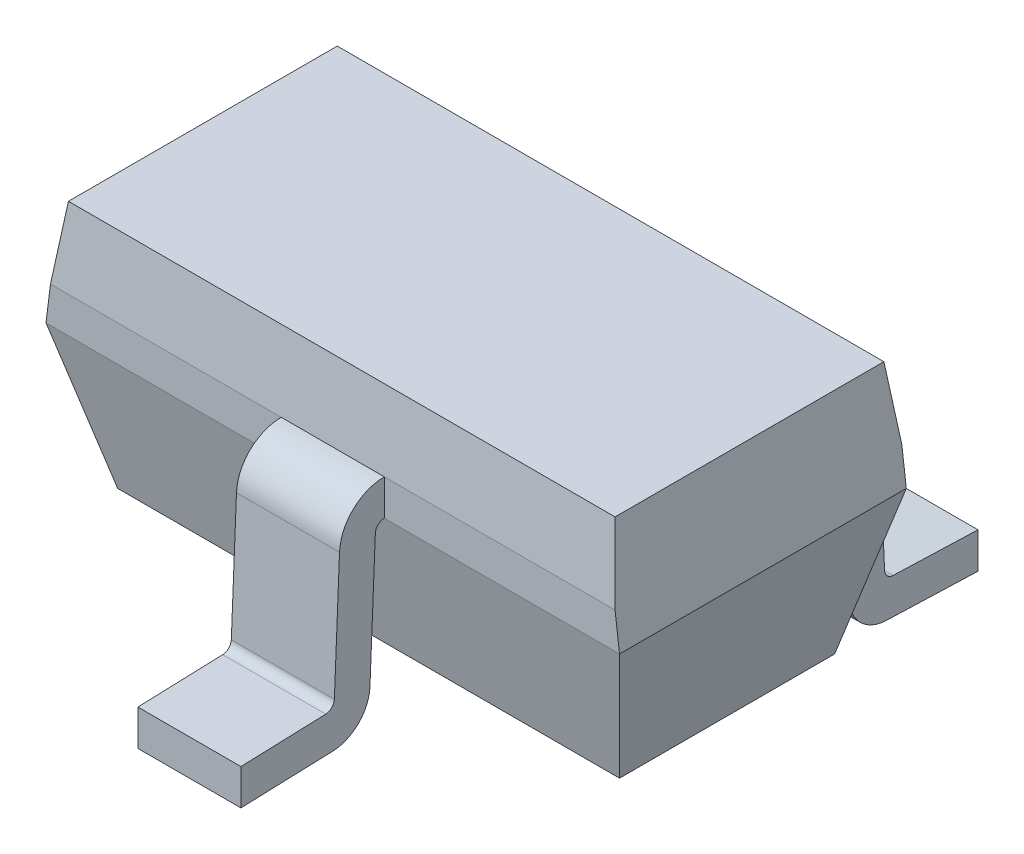
SolidWorks part; units mm, degrees
material "6061 Alloy"
ref_plane "Front" through (0, 0, 0) normal (0, 0, 1) x (1, 0, 0)
ref_plane "Top" through (0, 0, 0) normal (0, 1, 0) x (1, 0, 0)
ref_plane "Right" through (0, 0, 0) normal (1, 0, 0) x (0, 0, -1)
sketch "Sketch1" plane through (0, 0, 0) normal (1, 0, 0) x (0, 0, -1)
  line L0 (-0.8885, 0) -> (1.8018, 0) construction
  line L1 (-0.375, 0.8) -> (0.375, 0.8)
  line L2 (0, -0.5648) -> (0, 1.2045) construction
  line L3 (0.375, 0.8) -> (0.4, 0.6)
  line L4 (0.4, 0.5) -> (0.3, 0.1)
  line L5 (0.3, 0.1) -> (-0.3, 0.1)
  line L6 (0.5249, 0.4802) -> (0.5393, 0.1322)
  line L7 (0.5634, 0.1083) -> (0.8, 0.1)
  line L8 (0.8, 0.1) -> (0.8, 0)
  line L9 (0.5443, 0.0089) -> (0.8, 0)
  line L10 (0.44, 0.1126) -> (0.425, 0.476)
  line L11 (-0.44, 0.1126) -> (-0.425, 0.476)
  line L12 (-0.8, 0.1) -> (-0.8, 0)
  line L13 (-0.5634, 0.1083) -> (-0.8, 0.1)
  line L14 (-0.5249, 0.4802) -> (-0.5393, 0.1322)
  line L15 (-0.4, 0.5) -> (-0.3, 0.1)
  line L16 (-0.375, 0.8) -> (-0.4, 0.6)
  line L17 (-0.5443, 0.0089) -> (-0.8, 0)
  arc A0 (0.425, 0.476) -> (0.4, 0.5) centre (0.4, 0.475) ccw
  arc A1 (0.5249, 0.4802) -> (0.4, 0.6) centre (0.4, 0.475) ccw
  arc A2 (0.5249, 0.4802) -> (0.4, 0.6) centre (0.4, 0.475) ccw construction
  arc A3 (0.5443, 0.0089) -> (0.44, 0.1126) centre (0.5481, 0.117) cw
  arc A4 (0.5393, 0.1322) -> (0.5634, 0.1083) centre (0.5643, 0.1332) ccw
  arc A5 (-0.5393, 0.1322) -> (-0.5634, 0.1083) centre (-0.5643, 0.1332) cw
  arc A6 (-0.5443, 0.0089) -> (-0.44, 0.1126) centre (-0.5481, 0.117) ccw
  arc A7 (-0.5249, 0.4802) -> (-0.4, 0.6) centre (-0.4, 0.475) cw
  arc A8 (-0.425, 0.476) -> (-0.4, 0.5) centre (-0.4, 0.475) cw
  dimension "D9" = 0.1
  dimension "D7" = 0.025
  dimension "D1" = 0.75
  dimension "D2" = 0.8
  dimension "D3" = 0.6
  dimension "D4" = 0.1
  dimension "D5" = 0.8
  dimension "D6" = 0.3
  dimension "D8" = 2
  dimension "D10" = 0.36
  dimension "D11" = 1.6
  dimension "D12" = 0.4
  dimension "D13" = 0.1
  dimension "D14" = 0.1
extrude "Extrude1" add sketch "Sketch1" along normal mid plane 1.6
sketch "Sketch2" plane through (0, 0.8, 0) normal (0, 1, 0) x (1, 0, 0)
  line L0 (0.8, -0.4) -> (-0.8, -0.4) construction
  line L1 (0.1437, -0.4) -> (0.8, -0.4)
  line L2 (0.1437, -0.4) -> (0.1438, -0.8)
  line L3 (0.1438, -0.8) -> (0.8, -0.8)
  line L4 (0.8, -0.4) -> (0.8, -0.8)
  line L5 (0, -0.8836) -> (0, 0.9161) construction
  line L7 (-0.4, 0.4) -> (0.4, 0.4)
  line L8 (-0.4, 0.4) -> (-0.4, 0.8)
  line L9 (-0.4, 0.8) -> (0.4, 0.8)
  line L10 (0.4, 0.4) -> (0.4, 0.8)
  line L11 (0.8, 0.8) -> (-0.8, 0.8) construction
  line L12 (0.4, 0.6) -> (0.6, 0.6) construction
  line L13 (0.8, 0.8) -> (0.6, 0.8)
  line L14 (0.8, 0.8) -> (0.8, 0.4)
  line L15 (0.8, 0.4) -> (0.6, 0.4)
  line L16 (0.6, 0.8) -> (0.6, 0.4)
  line L17 (-0.8, 0.8) -> (-0.8, 0.4)
  line L18 (-0.8, 0.8) -> (-0.6, 0.8)
  line L19 (-0.6, 0.8) -> (-0.6, 0.4)
  line L20 (-0.8, 0.4) -> (-0.6, 0.4)
  line L21 (-0.8, -0.4) -> (-0.8, -0.8)
  line L22 (-0.1437, -0.4) -> (-0.8, -0.4)
  line L23 (-0.1437, -0.4) -> (-0.1438, -0.8)
  line L24 (-0.1438, -0.8) -> (-0.8, -0.8)
  line L25 (0.8, 0.4) -> (-0.8, 0.4) construction
  point P25 (0.5, 0.6)
  dimension "D1" = 0.2875
  dimension "D2" = 0.2
  dimension "D3" = 0.8
  dimension "D4" = 1
extrude "Cut-Extrude2" cut sketch "Sketch2" against normal through all
sketch "Sketch3" plane through (0, 0, 0) normal (0, 0, 1) x (1, 0, 0)
  line L0 (0.8, 0.6) -> (0.1437, 0.6) construction
  line L1 (0.8, 0.5) -> (0.1437, 0.5) construction
  line L2 (0.8, 0.8) -> (0.8, 0.6) construction
  line L3 (0.7625, 0.8) -> (0.8, 0.5)
  line L4 (0.8, 0.5) -> (0.7, 0.1)
  line L5 (0.8, 0.1) -> (-0.8, 0.1) construction
  line L6 (0.8, 0.8) -> (-0.8, 0.8) construction
  line L7 (0, -0.1376) -> (0, 0.9681) construction
  line L8 (0.7, 0.1) -> (0.8, 0.1)
  line L9 (0.8, 0.1) -> (0.8, 0.5)
  line L10 (0.7625, 0.8) -> (0.8, 0.8)
  line L11 (0.8, 0.8) -> (0.8, 0.5)
  line L12 (-0.7625, 0.8) -> (-0.8, 0.8)
  line L13 (-0.8, 0.8) -> (-0.8, 0.5)
  line L14 (-0.7625, 0.8) -> (-0.8, 0.5)
  line L15 (-0.8, 0.1) -> (-0.8, 0.5)
  line L16 (-0.8, 0.5) -> (-0.7, 0.1)
  line L17 (-0.7, 0.1) -> (-0.8, 0.1)
  dimension "D2" = 82.875
  dimension "D3" = 75.964
extrude "Cut-Extrude3" cut sketch "Sketch3" against normal through all and the other way through all contours L17 L16 L15 | L8 L9 L4 | L14 L12 L13 | L11 L10 L3
